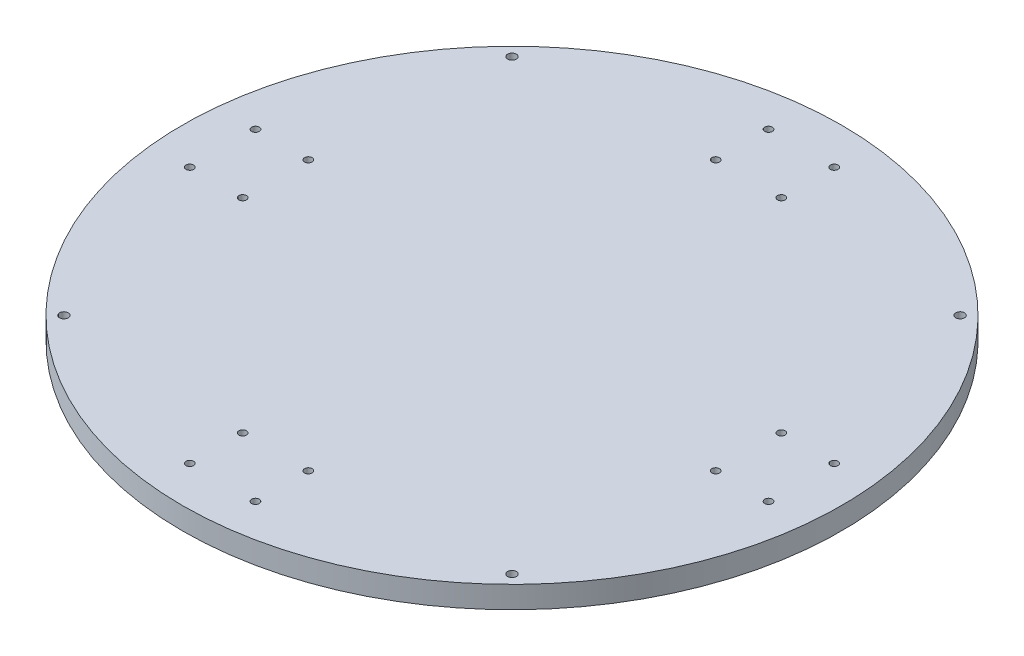
SolidWorks part; units mm, degrees
material "1060 Alloy"
ref_plane "Front Plane" through (0, 0, 0) normal (0, 0, 1) x (1, 0, 0)
ref_plane "Top Plane" through (0, 0, 0) normal (0, 1, 0) x (1, 0, 0)
ref_plane "Right Plane" through (0, 0, 0) normal (1, 0, 0) x (0, 0, -1)
sketch "Sketch1" plane through (0, 0, 0) normal (0, 1, 0) x (1, 0, 0)
  circle A0 centre (0, 0) radius 150
extrude "Boss-Extrude1" add sketch "Sketch1" along normal blind 10
sketch "Sketch2" plane through (0, 10, 0) normal (0, 1, 0) x (1, 0, 0)
  line L0 (0, 0) -> (-177.8464, 0) construction
  line L1 (0, 0) -> (0, 145.1898) construction
  line L2 (0, 0) -> (115.5258, 115.5258) construction
  circle A0 centre (-14.945, 131.7064) radius 1.73
  circle A1 centre (-14.945, 107.6464) radius 1.73
  circle A2 centre (14.945, 107.6464) radius 1.73
  circle A3 centre (14.945, 131.7064) radius 1.73
  circle A4 centre (131.7064, 14.945) radius 1.73
  circle A5 centre (131.7064, -14.945) radius 1.73
  circle A6 centre (107.6464, -14.945) radius 1.73
  circle A7 centre (107.6464, 14.945) radius 1.73
  circle A8 centre (14.945, -131.7064) radius 1.73
  circle A9 centre (-14.945, -131.7064) radius 1.73
  circle A10 centre (-14.945, -107.6464) radius 1.73
  circle A11 centre (14.945, -107.6464) radius 1.73
  circle A12 centre (-131.7064, -14.945) radius 1.73
  circle A13 centre (-131.7064, 14.945) radius 1.73
  circle A14 centre (-107.6464, 14.945) radius 1.73
  circle A15 centre (-107.6464, -14.945) radius 1.73
  circle A16 centre (101.9745, 101.9745) radius 2
  circle A17 centre (101.9745, -101.9745) radius 2
  circle A18 centre (-101.9745, -101.9745) radius 2
  circle A19 centre (-101.9745, 101.9745) radius 2
  point P39 (0, 0)
  point P49 (0, 0)
  dimension "D1" = 14.945
  dimension "D2" = 3.46
  dimension "D5" = 4
  dimension "D3" = 24.06
  dimension "D4" = 4
extrude "Cut-Extrude1" cut sketch "Sketch2" against normal blind 10
